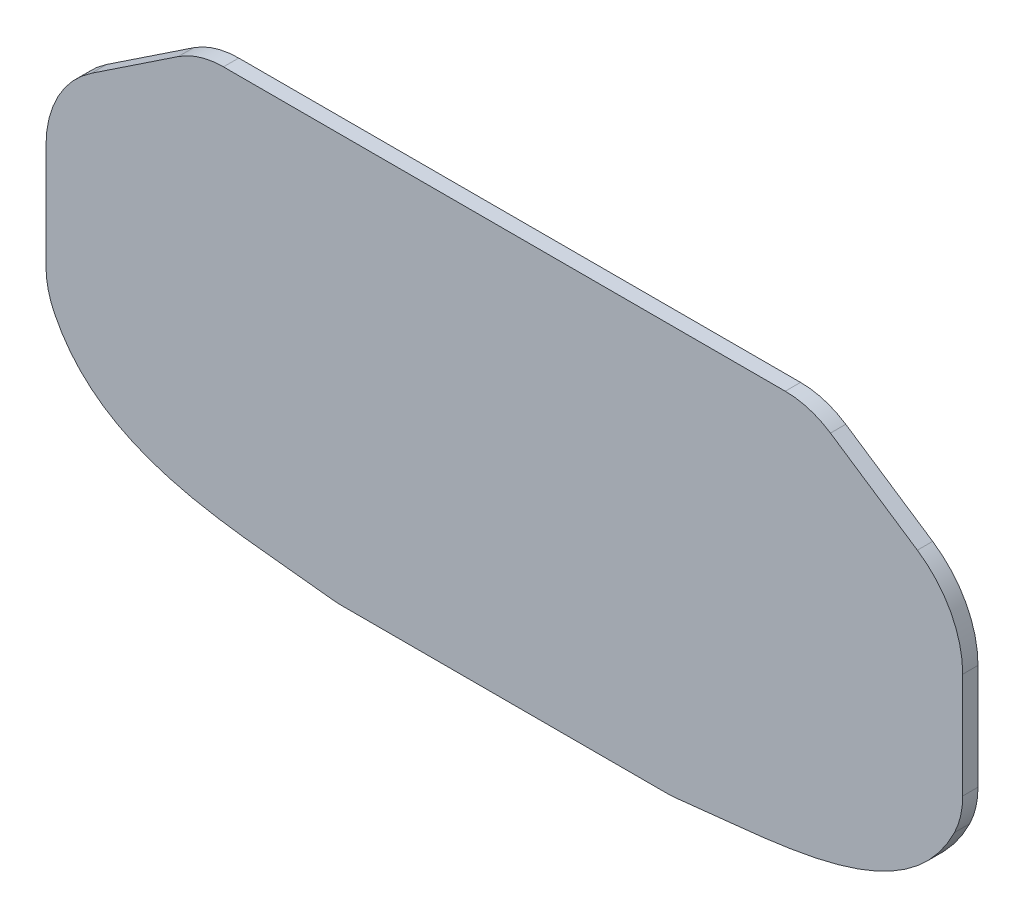
SolidWorks part; units mm, degrees
ref_plane "Front Plane" through (0, 0, 0) normal (0, 0, 1) x (1, 0, 0)
ref_plane "Top Plane" through (0, 0, 0) normal (0, 1, 0) x (1, 0, 0)
ref_plane "Right Plane" through (0, 0, 0) normal (1, 0, 0) x (0, 0, -1)
sketch "Sketch1" plane through (0, 0, 0) normal (0, 0, 1) x (1, 0, 0)
  line L0 (0, 76.2) -> (38.1, 101.6)
  line L1 (38.1, 101.6) -> (190.5, 101.6)
  line L2 (190.5, 101.6) -> (228.6, 76.2)
  line L3 (228.6, 76.2) -> (228.6, 0)
  line L4 (228.6, 0) -> (0, 0)
  line L5 (0, 0) -> (0, 76.2)
  point P8 (-2.9198, 1.6847)
  dimension "D1" = 152.4
  dimension "D2" = 38.1
  dimension "D3" = 38.1
  dimension "D4" = 25.4
  dimension "D5" = 25.4
  dimension "D6" = 101.6
extrude "Boss-Extrude1" add sketch "Sketch1" along normal blind 3.81 contours L1 L2 L3 L4 L5 L0
fillet "Fillet1" radius 20.32 2 edges at (38.1, 101.6, 1.905) (190.5, 101.6, 1.905)
fillet "Fillet3" radius 25.4 2 edges at (228.6, 76.2, 1.905) (0, 76.2, 1.905)
sketch "Sketch2" plane through (0, 0, 3.81) normal (0, 0, 1) x (1, 0, 0)
  line L0 (0, -55) -> (0, 55) construction
  line L2 (72.3248, 0) -> (0, 0)
  line L3 (0, 0) -> (0, 32.4837)
  line L4 (114.3, 123.048) -> (114.3, -17.9761) construction
  line L5 (156.2752, 0) -> (228.6, 0)
  line L6 (228.6, 0) -> (228.6, 32.4837)
  spline S0 degree 3 poles (0, 32.4837) (10.0595, 1.8404) (47.8361, 3.417) (72.3248, 0) knots 0 0 0 0 1 1 1 1
  spline S1 degree 3 poles (228.6, 32.4837) (218.5405, 1.8404) (180.7639, 3.417) (156.2752, 0) knots 0 0 0 0 1 1 1 1
  dimension "D1" = 114.3
extrude "Cut-Extrude8" cut sketch "Sketch2" against normal through all contours S0 L2 L3 | L5 L6 S1
fillet "Fillet4" radius 20.32 2 edges at (0, 32.4837, 1.905) (228.6, 32.4837, 1.905)
fillet "Fillet5" radius 20.32 2 edges at (156.2752, 0, 1.905) (72.3248, 0, 1.905)
